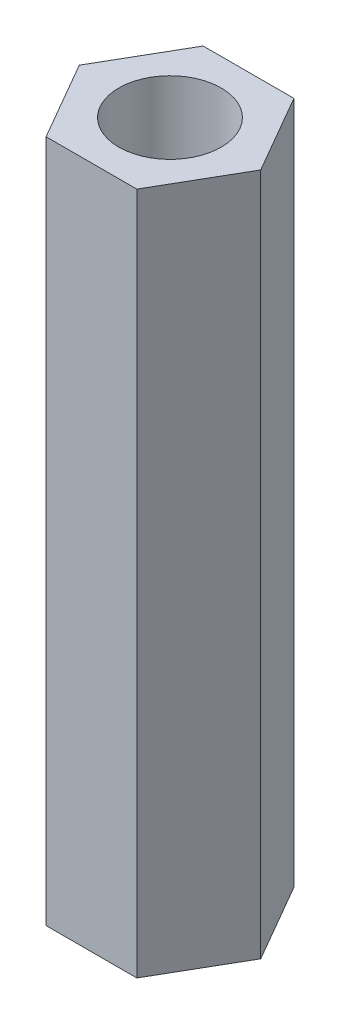
SolidWorks part; units mm, degrees
ref_plane "前视基准面" through (0, 0, 0) normal (0, 0, 1) x (1, 0, 0)
ref_plane "上视基准面" through (0, 0, 0) normal (0, 1, 0) x (1, 0, 0)
ref_plane "右视基准面" through (0, 0, 0) normal (1, 0, 0) x (0, 0, -1)
other "Configuration Table"
sketch "草图1" plane through (0, 0, 0) normal (0, 1, 0) x (1, 0, 0)
  line L1 (1.3279, -2.3) -> (2.6558, 0)
  line L2 (2.6558, 0) -> (1.3279, 2.3)
  line L3 (1.3279, 2.3) -> (-1.3279, 2.3)
  line L4 (-1.3279, 2.3) -> (-2.6558, 0)
  line L5 (-2.6558, 0) -> (-1.3279, -2.3)
  line L6 (-1.3279, -2.3) -> (1.3279, -2.3)
  circle A0 centre (0, 0) radius 1.5
  circle A1 centre (0, 0) radius 2.3 construction
  dimension "D2" = 3
  dimension "D1" = 4.6
extrude "凸台-拉伸1" add sketch "草图1" along normal blind 20
